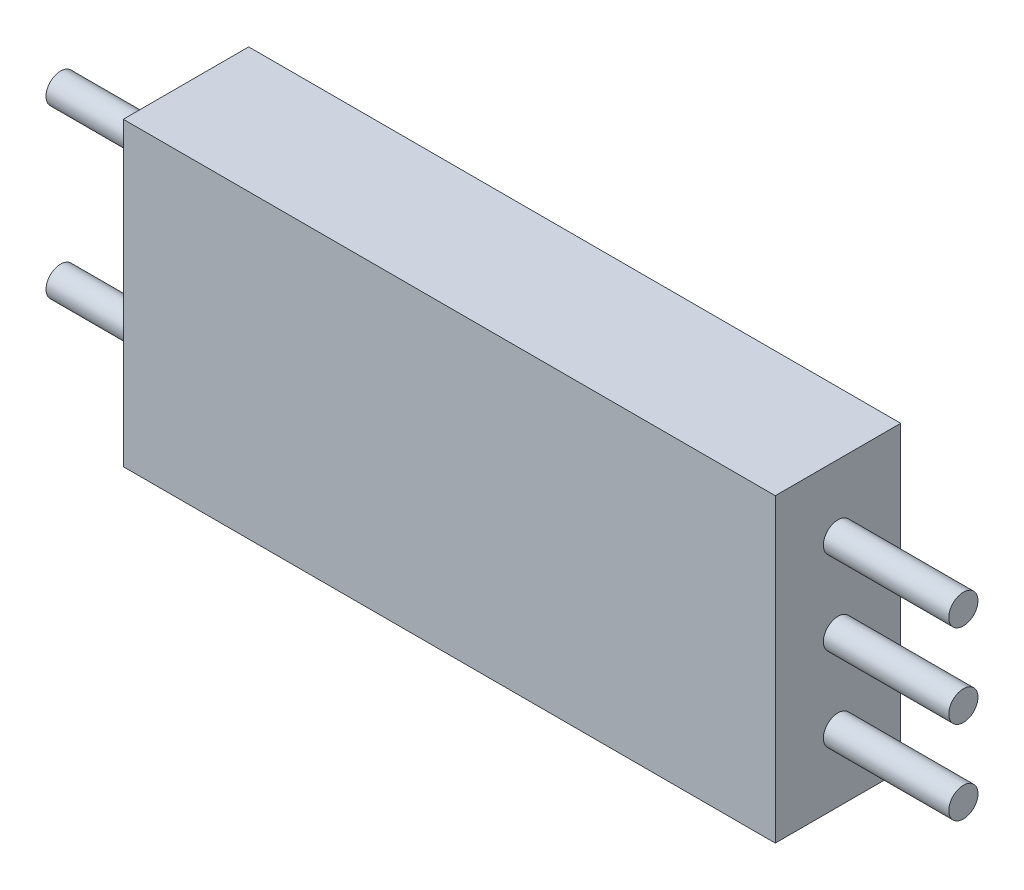
SolidWorks part; units mm, degrees
ref_plane "Front Plane" through (0, 0, 0) normal (0, 0, 1) x (1, 0, 0)
ref_plane "Top Plane" through (0, 0, 0) normal (0, 1, 0) x (1, 0, 0)
ref_plane "Right Plane" through (0, 0, 0) normal (1, 0, 0) x (0, 0, -1)
sketch "Эскиз2" plane through (0, 0, 0) normal (0, 0, 1) x (1, 0, 0)
  line L1 (-39, -18) -> (39, -18)
  line L2 (-39, -18) -> (-39, 18)
  line L3 (-39, 18) -> (39, 18)
  line L4 (39, -18) -> (39, 18)
  line L5 (-39, -18) -> (39, 18) construction
  line L6 (-39, 18) -> (39, -18) construction
  point P0 (0, 0)
  dimension "D1" = 78
  dimension "D2" = 36
extrude "Бобышка-Вытянуть1" add sketch "Эскиз2" along normal mid plane 15
sketch "Эскиз3" plane through (39, 0, 0) normal (1, 0, 0) x (0, 0, -1)
  line L0 (0, -18) -> (0, 18) construction
  line L1 (-7.5, -18) -> (7.5, -18) construction
  line L2 (-7.5, 18) -> (7.5, 18) construction
  circle A0 centre (0, -10) radius 1.75
  circle A1 centre (0, 0) radius 1.75
  circle A2 centre (0, 10) radius 1.75
  dimension "D1" = 3.5
  dimension "D2" = 10
  dimension "D3" = 10
extrude "Бобышка-Вытянуть2" add sketch "Эскиз3" along normal blind 15
sketch "Эскиз4" plane through (-39, 0, 0) normal (-1, 0, 0) x (0, 0, 1)
  line L0 (0, 18) -> (0, -18) construction
  line L1 (7.5, 18) -> (-7.5, 18) construction
  line L2 (7.5, -18) -> (-7.5, -18) construction
  circle A0 centre (0, 10) radius 1.75
  circle A1 centre (0, -10) radius 1.75
  dimension "D1" = 3.5
  dimension "D2" = 20
  dimension "D3" = 36
  dimension "D4" = 8
extrude "Бобышка-Вытянуть3" add sketch "Эскиз4" along normal blind 15
